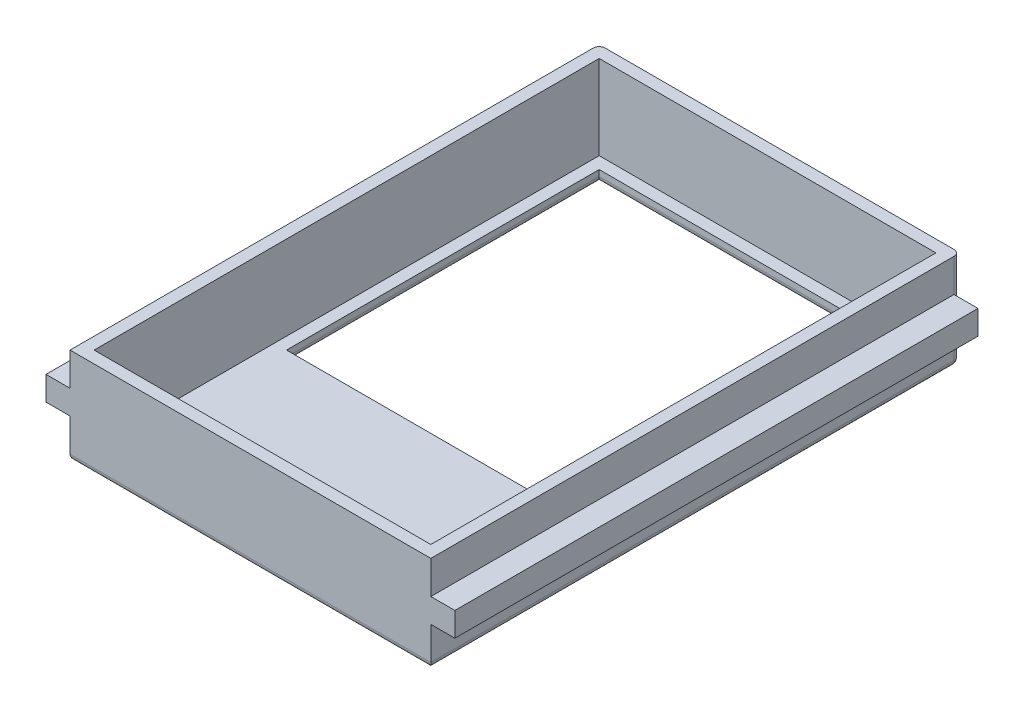
SolidWorks part; units mm, degrees
ref_plane "Front Plane" through (0, 0, 0) normal (0, 0, 1) x (1, 0, 0)
ref_plane "Top Plane" through (0, 0, 0) normal (0, 1, 0) x (1, 0, 0)
ref_plane "Right Plane" through (0, 0, 0) normal (1, 0, 0) x (0, 0, -1)
sketch "Sketch1" plane through (0, 0, 0) normal (0, 1, 0) x (1, 0, 0)
  line L1 (0, 0) -> (30, 0)
  line L2 (0, 0) -> (0, 44)
  line L3 (0, 44) -> (30, 44)
  line L4 (30, 0) -> (30, 44)
  dimension "D1" = 30
  dimension "D2" = 44
extrude "Boss-Extrude3" add sketch "Sketch1" along normal blind 1
sketch "Sketch3" plane through (0, 1, 0) normal (0, 1, 0) x (1, 0, 0)
  line L0 (0, 44) -> (0, 0) construction
  line L1 (2, 42) -> (28, 42)
  line L2 (2, 42) -> (2, 16)
  line L3 (2, 16) -> (28, 16)
  line L4 (28, 42) -> (28, 16)
  line L5 (30, 44) -> (0, 44) construction
  dimension "D1" = 26
  dimension "D2" = 26
  dimension "D3" = 2
  dimension "D4" = 2
extrude "Cut-Extrude1" cut sketch "Sketch3" against normal blind 1
sketch "Sketch4" plane through (0, 1, 0) normal (0, 1, 0) x (1, 0, 0)
  line L0 (0, 44) -> (0, 0) construction
  line L1 (1, 43) -> (29, 43)
  line L2 (1, 43) -> (1, 1)
  line L3 (1, 1) -> (29, 1)
  line L4 (29, 43) -> (29, 1)
  line L5 (0, 0) -> (30, 0) construction
  line L6 (30, 0) -> (30, 44) construction
  line L7 (30, 44) -> (0, 44) construction
  line L10 (0, 44) -> (30, 44)
  line L11 (0, 44) -> (0, 0)
  line L12 (0, 0) -> (30, 0)
  line L13 (30, 44) -> (30, 0)
  dimension "D1" = 1
  dimension "D2" = 1
  dimension "D3" = 1
  dimension "D4" = 1
extrude "Boss-Extrude4" add sketch "Sketch4" along normal blind 7
fillet "Fillet1" radius 0.5 10 edges at (15, 0, 0) (30, 0, -22) (15, 0, -44) (0, 0, -22) (30, 4, -44) (0, 4, -44) (15, 0, -42) (28, 0, -29) (15, 0, -16) (2, 0, -29)
sketch "Sketch5" plane through (0, 0, 0) normal (-1, 0, 0) x (0, 0, 1)
  line L7 (-43.5, 8) -> (-43.5, 0.5) construction
  line L8 (-43.5, 3.25) -> (0, 3.25)
  line L9 (-43.5, 3.25) -> (-43.5, 5.25)
  line L10 (-43.5, 5.25) -> (0, 5.25)
  line L11 (0, 3.25) -> (0, 5.25)
  line L12 (0, 8) -> (0, 0.5) construction
  line L14 (-43.5, 0.5) -> (0, 0.5) construction
  dimension "D1" = 2.75
  dimension "D2" = 2
extrude "Boss-Extrude5" add sketch "Sketch5" along normal blind 2
sketch "Sketch6" plane through (30, 0, 0) normal (1, 0, 0) x (0, 0, -1)
  line L0 (0, 8) -> (0, 0.5) construction
  line L1 (0, 5.25) -> (43.5, 5.25)
  line L2 (0, 5.25) -> (0, 3.25)
  line L3 (0, 3.25) -> (43.5, 3.25)
  line L4 (43.5, 5.25) -> (43.5, 3.25)
  line L5 (43.5, 0.5) -> (43.5, 8) construction
  line L6 (0, 8) -> (43.5, 8) construction
  dimension "D1" = 2
  dimension "D2" = 2.75
extrude "Boss-Extrude6" add sketch "Sketch6" along normal blind 2
